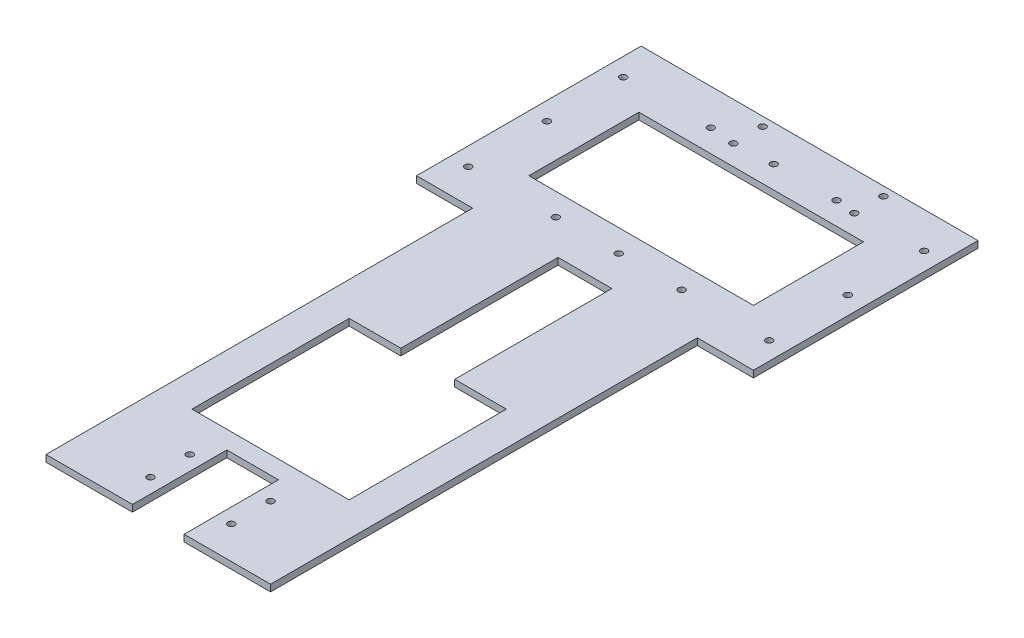
SolidWorks part; units mm, degrees
ref_plane "正面" through (0, 0, 0) normal (0, 0, 1) x (1, 0, 0)
ref_plane "平面" through (0, 0, 0) normal (0, 1, 0) x (1, 0, 0)
ref_plane "右側面" through (0, 0, 0) normal (1, 0, 0) x (0, 0, -1)
ref_plane "平面1" through (0, 0, 0) normal (0, -1, 0) x (1, 0, 0)
sketch "ｽｹｯﾁ1" plane through (0, 0, 0) normal (0, -1, 0) x (1, 0, 0)
  line L0 (100, -215) -> (100, -264)
  line L1 (100, -264) -> (0, -264)
  line L2 (0, -264) -> (0, -215)
  line L3 (0, -215) -> (100, -215)
  line L4 (85, -50) -> (85, -120)
  line L5 (85, -120) -> (62, -120)
  line L6 (62, -120) -> (62, -190)
  line L7 (62, -190) -> (38, -190)
  line L8 (38, -190) -> (38, -120)
  line L9 (38, -120) -> (15, -120)
  line L10 (15, -120) -> (15, -50)
  line L11 (15, -50) -> (85, -50)
  line L12 (61.5, -42) -> (38.5, -42)
  line L13 (38.5, -42) -> (38.5, 0)
  line L14 (38.5, 0) -> (0, 0)
  line L15 (0, 0) -> (0, -190)
  line L16 (0, -190) -> (-25, -190)
  line L17 (-25, -190) -> (-25, -290)
  line L18 (-25, -290) -> (125, -290)
  line L19 (125, -290) -> (125, -190)
  line L20 (125, -190) -> (100, -190)
  line L21 (100, -190) -> (100, 0)
  line L22 (100, 0) -> (61.5, 0)
  line L23 (61.5, 0) -> (61.5, -42)
  circle A0 centre (33.1, -286) radius 1.5
  circle A1 centre (86.9, -286) radius 1.5
  circle A2 centre (-17, -274) radius 1.5
  circle A3 centre (50, -274) radius 1.5
  circle A4 centre (117, -274) radius 1.5
  circle A5 centre (78, -205) radius 1.5
  circle A6 centre (22, -205) radius 1.5
  circle A7 centre (68, -14.5) radius 1.5
  circle A8 centre (32, -32) radius 1.5
  circle A9 centre (32, -14.5) radius 1.5
  circle A10 centre (68, -32) radius 1.5
  circle A11 centre (-17, -205) radius 1.5
  circle A12 centre (50, -205) radius 1.5
  circle A13 centre (117, -205) radius 1.5
  circle A14 centre (78, -274) radius 1.5
  circle A15 centre (22, -274) radius 1.5
  circle A16 centre (86.9, -273) radius 1.5
  circle A17 centre (33.1, -273) radius 1.5
  circle A18 centre (117, -240) radius 1.5
  circle A19 centre (-17, -240) radius 1.5
extrude "ﾎﾞｽ - 押し出し1" add sketch "ｽｹｯﾁ1" against normal blind 3
